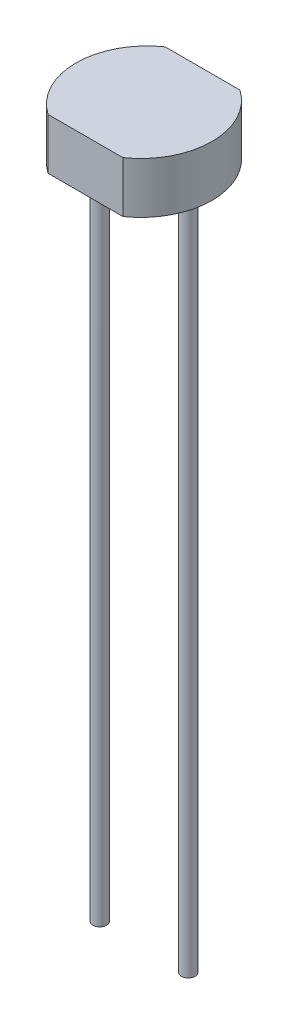
SolidWorks part; units mm, degrees
ref_plane "Front Plane" through (0, 0, 0) normal (0, 0, 1) x (1, 0, 0)
ref_plane "Top Plane" through (0, 0, 0) normal (0, 1, 0) x (1, 0, 0)
ref_plane "Right Plane" through (0, 0, 0) normal (1, 0, 0) x (0, 0, -1)
sketch "Sketch1" plane through (0, 0, 0) normal (0, 1, 0) x (1, 0, 0)
  line L0 (0.1188, 0) -> (-0.1188, 0) construction
  line L1 (-1.397, 2.1844) -> (1.397, 2.1844)
  line L2 (0, 2.1844) -> (0, -2.1844) construction
  line L3 (-1.397, -2.1844) -> (1.397, -2.1844)
  arc A0 (-1.397, 2.1844) -> (-1.397, -2.1844) centre (0.1188, 0) ccw
  arc A1 (1.397, 2.1844) -> (1.397, -2.1844) centre (-0.1188, 0) cw
  point P2 (0, 0)
  point P7 (0, 0)
  point P9 (0, 2.1844)
  point P14 (-2.54, 0)
  point P15 (2.54, 0)
  dimension "D2" = 5.08
  dimension "D1" = 4.3688
  dimension "D3" = 2.794
extrude "Boss-Extrude1" add sketch "Sketch1" along normal blind 1.905
sketch "Sketch2" plane through (0, 0, 0) normal (0, -1, 0) x (1, 0, 0)
  line L0 (0, 0) -> (0, 0.8227) construction
  circle A0 centre (-1.651, 0) radius 0.254
  circle A1 centre (1.651, 0) radius 0.254
  dimension "D1" = 0.508
  dimension "D2" = 3.302
extrude "Boss-Extrude2" add sketch "Sketch2" along normal blind 25.4
